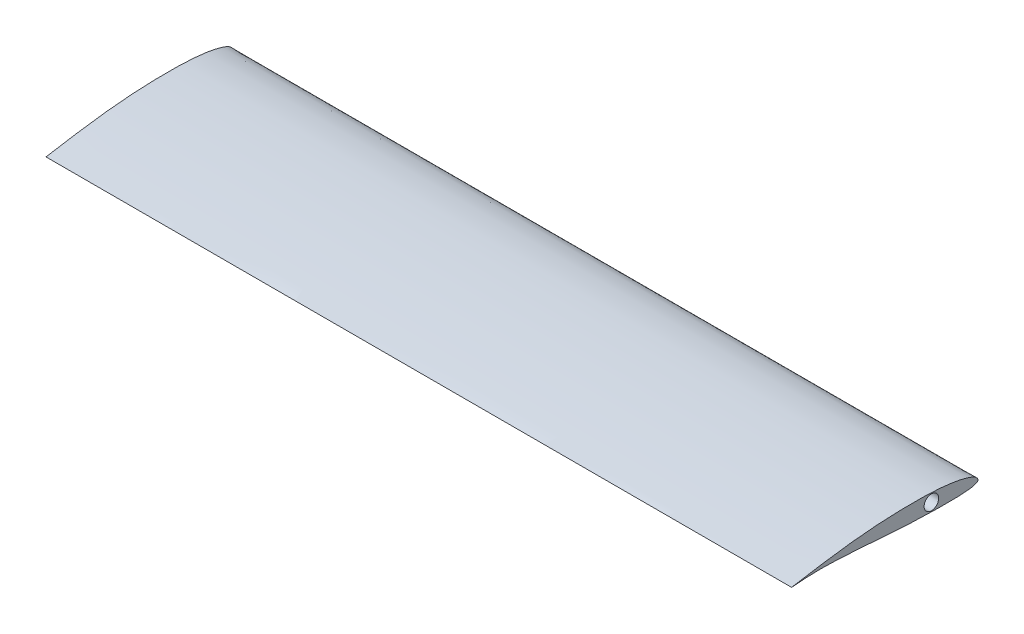
SolidWorks part; units mm, degrees
ref_plane "Piano frontale" through (0, 0, 0) normal (0, 0, 1) x (1, 0, 0)
ref_plane "Piano superiore" through (0, 0, 0) normal (0, 1, 0) x (1, 0, 0)
ref_plane "Piano destro" through (0, 0, 0) normal (1, 0, 0) x (0, 0, -1)
curve "Curva1"
  spline degree 3 poles (0, 0.1586, 228.4222) (0, -0.0487, 230.3931) (0, 0.2265, 228.4621) (0, 0.5086, 226.913) (0, 1.1462, 223.2123) (0, 1.931, 218.7267) (0, 2.9273, 212.8543) (0, 3.9498, 206.059) (0, 5.2727, 198.3155) (0, 6.561, 189.7964) (0, 7.9418, 180.47) (0, 9.3069, 170.5242) (0, 10.6253, 160.0699) (0, 11.8511, 149.2161) (0, 12.9346, 138.0666) (0, 13.8481, 126.7243) (0, 14.5595, 115.2867) (0, 15.0727, 103.8577) (0, 15.3886, 92.5492) (0, 15.5156, 81.4816) (0, 15.4486, 70.7769) (0, 15.1745, 60.5512) (0, 14.684, 50.9063) (0, 13.9467, 41.9272) (0, 12.97, 33.6788) (0, 11.7653, 26.2174) (0, 10.3812, 19.5949) (0, 8.87, 13.8689) (0, 7.2805, 9.0905) (0, 5.6287, 5.3083) (0, 3.8993, 2.5106) (0, 2.1212, 0.7476) (0, 0.7292, 0.0287) (0, -0.3776, -0.0196) (0, -1.5746, 0.4553) (0, -2.6365, 2.4153) (0, -3.7172, 5.2419) (0, -4.5344, 9.2662) (0, -5.1496, 14.3761) (0, -5.5312, 20.6192) (0, -5.7638, 27.933) (0, -5.8709, 36.2454) (0, -5.8469, 45.4468) (0, -5.721, 55.4256) (0, -5.4718, 66.0577) (0, -5.0939, 77.2256) (0, -4.5435, 88.8224) (0, -3.8205, 100.7584) (0, -2.962, 112.9458) (0, -2.0157, 125.2822) (0, -1.0562, 137.6465) (0, -0.1474, 149.8969) (0, 0.6495, 161.8774) (0, 1.2784, 173.4199) (0, 1.6866, 184.3415) (0, 1.8102, 194.4306) (0, 1.6774, 203.4894) (0, 1.3775, 211.306) (0, 0.9882, 217.8619) (0, 0.6308, 222.8142) (0, 0.284, 226.7967) (0, 0.1586, 228.4222) (0, -0.0487, 230.3931) (0, 0.2265, 228.4621) knots -0.014202 -0.006329 -0.001589 0 0.001576 0.006211 0.01368 0.023764 0.036307 0.051658 0.068045 0.086769 0.107053 0.128647 0.151303 0.174786 0.19886 0.223309 0.247929 0.272522 0.296848 0.320648 0.343669 0.365658 0.3864 0.405741 0.423561 0.439779 0.454311 0.467034 0.477831 0.486643 0.493542 0.498786 0.50271 0.50309 0.505896 0.510322 0.516831 0.525521 0.536535 0.549945 0.565696 0.583577 0.603379 0.624844 0.647727 0.671743 0.696673 0.722357 0.748609 0.77521 0.801891 0.828329 0.854175 0.879074 0.902636 0.924421 0.943939 0.960827 0.974827 0.985798 0.993671 0.998411 1 1.001576 1.006211 1.01368 periodic
sketch "Schizzo1" plane through (0, 0, 0) normal (1, 0, 0) x (0, 0, -1)
  line L0 (0, 0) -> (-57.5, 0) construction
  line L1 (-57.5, 15.0049) -> (-57.5, -5.6626) construction
  circle A0 centre (-57.5, 4.6711) radius 9
  spline S0 degree 3 poles (-228.4621, 0.2265) (-230.3931, -0.0487) (-228.4222, 0.1586) (-226.7967, 0.284) (-222.8142, 0.6308) (-217.8619, 0.9882) (-211.306, 1.3775) (-203.4894, 1.6774) (-194.4306, 1.8102) (-184.3415, 1.6866) (-173.4199, 1.2784) (-161.8774, 0.6495) (-149.8969, -0.1474) (-137.6465, -1.0562) (-125.2822, -2.0157) (-112.9458, -2.962) (-100.7584, -3.8205) (-88.8224, -4.5435) (-77.2256, -5.0939) (-66.0577, -5.4718) (-55.4256, -5.721) (-45.4468, -5.8469) (-36.2454, -5.8709) (-27.933, -5.7638) (-20.6192, -5.5312) (-14.3761, -5.1496) (-9.2662, -4.5344) (-5.2419, -3.7172) (-2.4153, -2.6365) (-0.4553, -1.5746) (0.0196, -0.3776) (-0.0287, 0.7292) (-0.7476, 2.1212) (-2.5106, 3.8993) (-5.3083, 5.6287) (-9.0905, 7.2805) (-13.8689, 8.87) (-19.5949, 10.3812) (-26.2174, 11.7653) (-33.6788, 12.97) (-41.9272, 13.9467) (-50.9063, 14.684) (-60.5512, 15.1745) (-70.7769, 15.4486) (-81.4816, 15.5156) (-92.5492, 15.3886) (-103.8577, 15.0727) (-115.2867, 14.5595) (-126.7243, 13.8481) (-138.0666, 12.9346) (-149.2161, 11.8511) (-160.0699, 10.6253) (-170.5242, 9.3069) (-180.47, 7.9418) (-189.7964, 6.561) (-198.3155, 5.2727) (-206.059, 3.9498) (-212.8543, 2.9273) (-218.7267, 1.931) (-223.2123, 1.1462) (-226.913, 0.5086) (-228.4621, 0.2265) (-230.3931, -0.0487) (-228.4222, 0.1586) knots -0.01368 -0.006211 -0.001576 0 0.001589 0.006329 0.014202 0.025173 0.039173 0.056061 0.075579 0.097364 0.120926 0.145825 0.171671 0.198109 0.22479 0.251391 0.277643 0.303327 0.328257 0.352273 0.375156 0.396621 0.416423 0.434304 0.450055 0.463465 0.474479 0.483169 0.489678 0.494104 0.49691 0.49729 0.501214 0.506458 0.513357 0.522169 0.532966 0.545689 0.560221 0.576439 0.594259 0.6136 0.634342 0.656331 0.679352 0.703152 0.727478 0.752071 0.776691 0.80114 0.825214 0.848697 0.871353 0.892947 0.913231 0.931955 0.948342 0.963693 0.976236 0.98632 0.993789 0.998424 1 1.001589 1.006329 1.014202 only from (-230, 0) to (-230, 0) construction
  spline S1 degree 3 poles (-228.4621, 0.2265) (-230.3931, -0.0487) (-228.4222, 0.1586) (-226.7967, 0.284) (-222.8142, 0.6308) (-217.8619, 0.9882) (-211.306, 1.3775) (-203.4894, 1.6774) (-194.4306, 1.8102) (-184.3415, 1.6866) (-173.4199, 1.2784) (-161.8774, 0.6495) (-149.8969, -0.1474) (-137.6465, -1.0562) (-125.2822, -2.0157) (-112.9458, -2.962) (-100.7584, -3.8205) (-88.8224, -4.5435) (-77.2256, -5.0939) (-66.0577, -5.4718) (-55.4256, -5.721) (-45.4468, -5.8469) (-36.2454, -5.8709) (-27.933, -5.7638) (-20.6192, -5.5312) (-14.3761, -5.1496) (-9.2662, -4.5344) (-5.2419, -3.7172) (-2.4153, -2.6365) (-0.4553, -1.5746) (0.0196, -0.3776) (-0.0287, 0.7292) (-0.7476, 2.1212) (-2.5106, 3.8993) (-5.3083, 5.6287) (-9.0905, 7.2805) (-13.8689, 8.87) (-19.5949, 10.3812) (-26.2174, 11.7653) (-33.6788, 12.97) (-41.9272, 13.9467) (-50.9063, 14.684) (-60.5512, 15.1745) (-70.7769, 15.4486) (-81.4816, 15.5156) (-92.5492, 15.3886) (-103.8577, 15.0727) (-115.2867, 14.5595) (-126.7243, 13.8481) (-138.0666, 12.9346) (-149.2161, 11.8511) (-160.0699, 10.6253) (-170.5242, 9.3069) (-180.47, 7.9418) (-189.7964, 6.561) (-198.3155, 5.2727) (-206.059, 3.9498) (-212.8543, 2.9273) (-218.7267, 1.931) (-223.2123, 1.1462) (-226.913, 0.5086) (-228.4621, 0.2265) (-230.3931, -0.0487) (-228.4222, 0.1586) knots -0.01368 -0.006211 -0.001576 0 0.001589 0.006329 0.014202 0.025173 0.039173 0.056061 0.075579 0.097364 0.120926 0.145825 0.171671 0.198109 0.22479 0.251391 0.277643 0.303327 0.328257 0.352273 0.375156 0.396621 0.416423 0.434304 0.450055 0.463465 0.474479 0.483169 0.489678 0.494104 0.49691 0.49729 0.501214 0.506458 0.513357 0.522169 0.532966 0.545689 0.560221 0.576439 0.594259 0.6136 0.634342 0.656331 0.679352 0.703152 0.727478 0.752071 0.776691 0.80114 0.825214 0.848697 0.871353 0.892947 0.913231 0.931955 0.948342 0.963693 0.976236 0.98632 0.993789 0.998424 1 1.001589 1.006329 1.014202 only from (-230, 0) to (-230, 0)
  dimension "D2" = 18
  dimension "D1" = 57.5
extrude "Estrusione-Estrusione1" add sketch "Schizzo1" along normal blind 920
